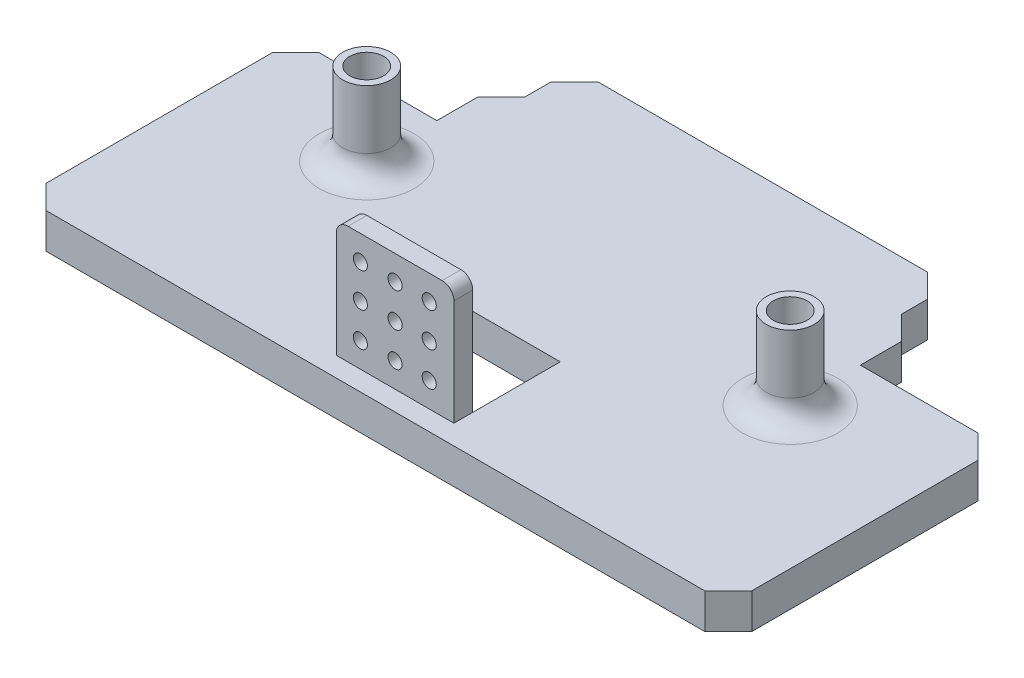
SolidWorks part; units mm, degrees
ref_plane "Front Plane" through (0, 0, 0) normal (0, 0, 1) x (1, 0, 0)
ref_plane "Top Plane" through (0, 0, 0) normal (0, 1, 0) x (1, 0, 0)
ref_plane "Right Plane" through (0, 0, 0) normal (1, 0, 0) x (0, 0, -1)
sketch "Sketch1" plane through (0, 0, 0) normal (0, 1, 0) x (1, 0, 0)
  line L1 (-75, 28.66) -> (75, 28.66)
  line L2 (-75, 28.66) -> (-75, -28.66)
  line L3 (-75, -28.66) -> (75, -28.66)
  line L4 (75, 28.66) -> (75, -28.66)
  line L5 (-75, 28.66) -> (75, -28.66) construction
  line L6 (-75, -28.66) -> (75, 28.66) construction
  point P0 (0, 0)
  dimension "D1" = 57.32
  dimension "D2" = 150
extrude "Boss-Extrude1" add sketch "Sketch1" along normal blind 7.5
sketch "Sketch2" plane through (0, 7.5, 0) normal (0, 1, 0) x (1, 0, 0)
  line L0 (-75, 0) -> (75, 0) construction
  line L1 (-75, 28.66) -> (-75, -28.66) construction
  line L2 (75, -28.66) -> (75, 28.66) construction
  circle A0 centre (-45, 0) radius 5.1
  circle A1 centre (45, 0) radius 5.1
  dimension "D1" = 30
  dimension "D2" = 30
extrude "Boss-Extrude2" add sketch "Sketch2" along normal blind 17.5
fillet "Fillet1" radius 5 2 edges at (45, 7.5, 5.1) (-45, 7.5, 5.1)
sketch "Sketch3" plane through (0, 25, 0) normal (0, 1, 0) x (1, 0, 0)
  circle A0 centre (-45, 0) radius 3.6
  circle A1 centre (45, 0) radius 3.6
extrude "Cut-Extrude1" cut sketch "Sketch3" against normal blind 25
sketch "Sketch4" plane through (0, 0, -28.66) normal (0, 0, -1) x (-1, 0, 0)
  line L0 (-75, 0) -> (75, 0) construction
  line L1 (-75, 7.5) -> (-45, 7.5)
  line L2 (-75, 7.5) -> (-75, 0)
  line L3 (-75, 0) -> (-45, 0)
  line L4 (-45, 7.5) -> (-45, 0)
  line L6 (75, 7.5) -> (45, 7.5)
  line L7 (75, 7.5) -> (75, 0)
  line L8 (75, 0) -> (45, 0)
  line L9 (45, 7.5) -> (45, 0)
  dimension "D1" = 30
  dimension "D2" = 30
extrude "Cut-Extrude2" cut sketch "Sketch4" against normal blind 13.75
chamfer "Chamfer1" distance 5 angle 45 4 edges at (75, 3.75, -14.91) (45, 3.75, -28.66) (-45, 3.75, -28.66) (-75, 3.75, -14.91)
sketch "Sketch5" plane through (0, 0, -28.66) normal (0, 0, -1) x (-1, 0, 0)
  line L1 (-40, 7.5) -> (40, 7.5)
  line L2 (-40, 7.5) -> (-40, 0)
  line L3 (-40, 0) -> (40, 0)
  line L4 (40, 7.5) -> (40, 0)
extrude "Boss-Extrude3" add sketch "Sketch5" along normal blind 10.5
chamfer "Chamfer2" distance 5 angle 45 2 edges at (40, 3.75, -39.16) (-40, 3.75, -39.16)
sketch "Sketch6" plane through (0, 0, -39.16) normal (0, 0, -1) x (-1, 0, 0)
  line L0 (-35, 3.75) -> (35, 3.75) construction
  line L1 (-35, 7.5) -> (-35, 0) construction
  line L2 (35, 0) -> (35, 7.5) construction
  circle A0 centre (-15, 3.75) radius 1.5
  circle A1 centre (15, 3.75) radius 1.5
  point P10 (0, 3.75)
  dimension "D1" = 15
  dimension "D2" = 15
extrude "Cut-Extrude3" cut sketch "Sketch6" against normal blind 7.5
sketch "Sketch11" plane through (0, 0, 28.66) normal (0, 0, 1) x (1, 0, 0)
  line L1 (-75, 7.5) -> (75, 7.5)
  line L2 (-75, 7.5) -> (-75, 0)
  line L3 (-75, 0) -> (75, 0)
  line L4 (75, 7.5) -> (75, 0)
extrude "Boss-Extrude5" add sketch "Sketch11" along normal blind 14.5
chamfer "Chamfer3" distance 5 angle 45 2 edges at (75, 3.75, 43.16) (-75, 3.75, 43.16)
sketch "Sketch12" plane through (0, 7.5, 0) normal (0, 1, 0) x (1, 0, 0)
  line L0 (0, 39.16) -> (0, -43.16) construction
  line L1 (-35, 39.16) -> (35, 39.16) construction
  line L2 (70, -43.16) -> (-70, -43.16) construction
  line L3 (-23.5, -28.17) -> (-8.5, -28.17) construction
  line L4 (0, -34.97) -> (-12.5, -34.97) construction
  line L5 (0, -34.97) -> (12.5, -34.97) construction
  line L6 (-12.5, -38.97) -> (12.5, -38.97) construction
  line L8 (-12.5, -34.97) -> (12.5, -34.97)
  line L9 (-12.5, -34.97) -> (-12.5, -38.97)
  line L10 (-12.5, -38.97) -> (12.5, -38.97)
  line L11 (12.5, -34.97) -> (12.5, -38.97)
  dimension "D1" = 67.33
  dimension "D2" = 8.5
  dimension "D3" = 15
  dimension "D4" = 6.8
  dimension "D5" = 12.5
  dimension "D6" = 12.5
  dimension "D7" = 4
extrude "Boss-Extrude6" add sketch "Sketch12" along normal blind 25
sketch "Sketch13" plane through (0, 7.5, 0) normal (0, 1, 0) x (1, 0, 0)
  line L0 (-12.5, -34.97) -> (-12.5, -16.37) construction
  line L10 (-12.5, -16.37) -> (12.5, -16.37)
  line L11 (-12.5, -16.37) -> (-12.5, -34.97)
  line L12 (-12.5, -34.97) -> (12.5, -34.97)
  line L13 (12.5, -16.37) -> (12.5, -34.97)
  dimension "D1" = 18.6
extrude "Cut-Extrude4" cut sketch "Sketch13" against normal blind 7.5
sketch "Sketch14" plane through (0, 0, 34.97) normal (0, 0, -1) x (-1, 0, 0)
  line L0 (12.5, 31) -> (-12.5, 31) construction
  line L1 (12.5, 32.5) -> (12.5, 7.5) construction
  line L2 (-12.5, 32.5) -> (-12.5, 7.5) construction
  line L3 (12.5, 32.5) -> (-12.5, 32.5) construction
  line L4 (12.5, 9) -> (-12.5, 9) construction
  line L5 (12.5, 7.5) -> (-12.5, 7.5) construction
  line L6 (11, 32.5) -> (11, 7.5) construction
  line L7 (-70, 7.5) -> (70, 7.5) construction
  line L8 (-11, 32.5) -> (-11, 7.5) construction
  line L9 (0, 31) -> (0, 9) construction
  line L10 (3.75, 31) -> (3.75, 9) construction
  line L11 (-3.75, 31) -> (-3.75, 9) construction
  line L12 (11, 23.5) -> (-11, 23.5) construction
  line L13 (11, 16.5) -> (-11, 16.5) construction
  line L14 (3.75, 20) -> (11, 20) construction
  line L15 (11, 27.25) -> (-11, 27.25) construction
  line L16 (11, 12.75) -> (-11, 12.75) construction
  line L17 (-7.25, 31) -> (-7.25, 9) construction
  circle A0 centre (7.375, 20) radius 1.5
  circle A1 centre (7.375, 27.25) radius 1.5
  circle A2 centre (7.375, 12.75) radius 1.5
  circle A3 centre (-7.25, 27.25) radius 1.5
  circle A4 centre (0, 27.25) radius 1.5
  circle A5 centre (0, 20) radius 1.5
  circle A6 centre (0, 12.75) radius 1.5
  circle A7 centre (-7.25, 12.75) radius 1.5
  circle A8 centre (-7.25, 20) radius 1.5
  dimension "D9" = 3.75
  dimension "D10" = 3.75
  dimension "D11" = 3.75
  dimension "D1" = 1.5
  dimension "D2" = 1.5
  dimension "D3" = 1.5
  dimension "D4" = 1.5
  dimension "D5" = 3.75
  dimension "D6" = 3.75
  dimension "D7" = 7.5
  dimension "D8" = 7.5
extrude "Cut-Extrude5" cut sketch "Sketch14" against normal blind 4
fillet "Fillet2" radius 2.5 2 edges at (12.5, 32.5, 36.97) (-12.5, 32.5, 36.97)
